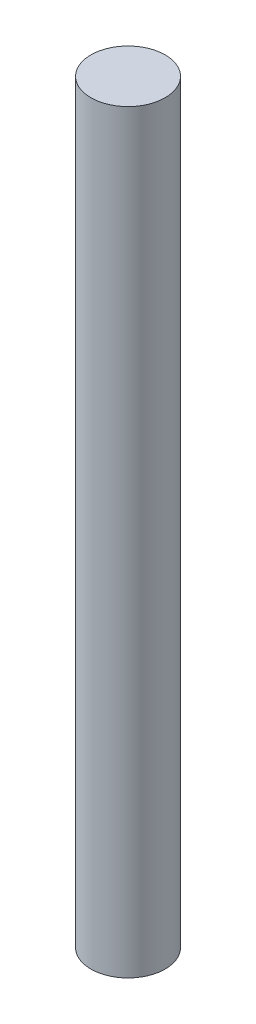
SolidWorks part; units mm, degrees
ref_plane "Front Plane" through (0, 0, 0) normal (0, 0, 1) x (1, 0, 0)
ref_plane "Top Plane" through (0, 0, 0) normal (0, 1, 0) x (1, 0, 0)
ref_plane "Right Plane" through (0, 0, 0) normal (1, 0, 0) x (0, 0, -1)
sketch "Sketch1" plane through (0, 0, 0) normal (0, 1, 0) x (1, 0, 0)
  circle A0 centre (0, 0) radius 7.5
  dimension "D1" = 15
extrude "Boss-Extrude1" add sketch "Sketch1" along normal blind 152.4
